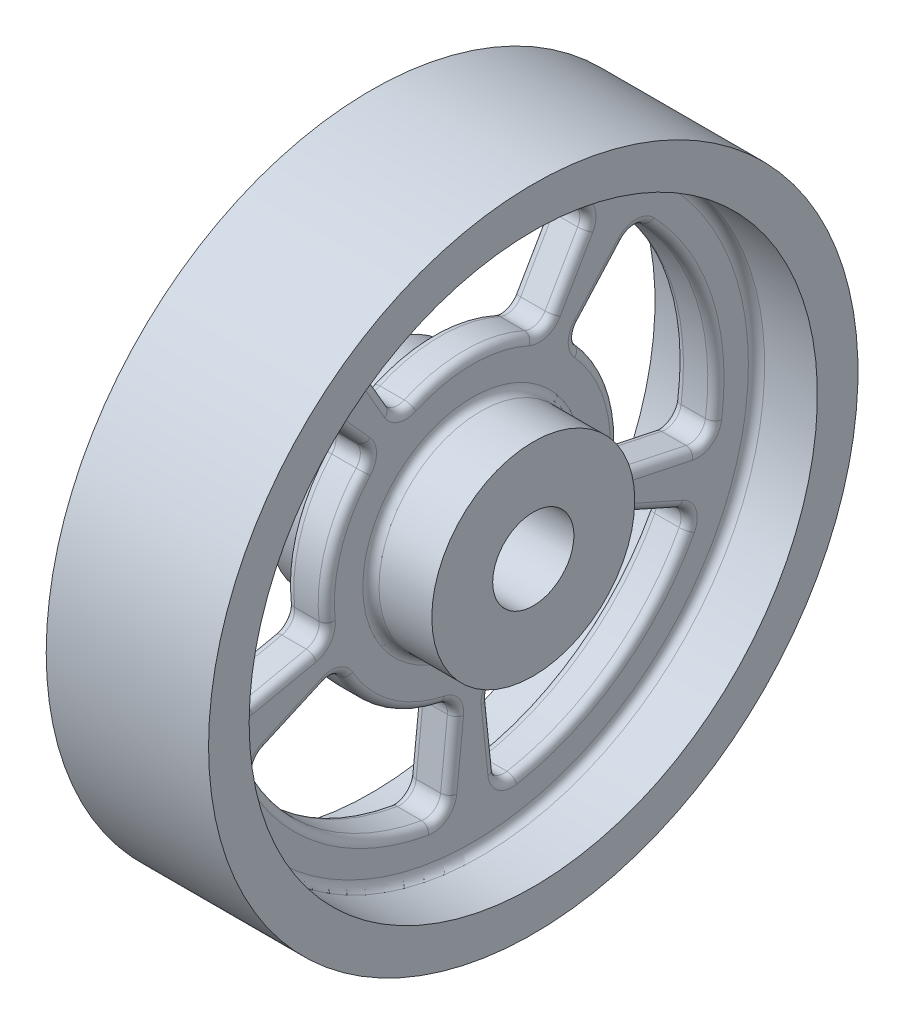
SolidWorks part; units mm, degrees
ref_plane "Front Plane" through (0, 0, 0) normal (0, 0, 1) x (1, 0, 0)
ref_plane "Top Plane" through (0, 0, 0) normal (0, 1, 0) x (1, 0, 0)
ref_plane "Right Plane" through (0, 0, 0) normal (1, 0, 0) x (0, 0, -1)
sketch "Sketch1" plane through (0, 0, 0) normal (0, 1, 0) x (1, 0, 0)
  line L0 (0, 0) -> (25.6742, 0) construction
  line L1 (0, 0) -> (0, 10.3933) construction
  line L2 (2.5, 35) -> (10, 35)
  line L3 (-10, 12.5) -> (-2.5, 12.5)
  line L4 (-10, 12.5) -> (-10, 5)
  line L5 (-10, 5) -> (10, 5)
  line L6 (10, 12.5) -> (10, 5)
  line L8 (-2.5, 12.5) -> (-2.5, 35)
  line L10 (2.5, 12.5) -> (2.5, 35)
  line L11 (-10, 40) -> (10, 40)
  line L12 (-10, 40) -> (-10, 35)
  line L13 (-10, 35) -> (-2.5, 35)
  line L14 (10, 40) -> (10, 35)
  line L15 (2.5, 12.5) -> (10, 12.5)
  dimension "D1" = 10
  dimension "D2" = 80
  dimension "D3" = 5
  dimension "D4" = 25
  dimension "D5" = 20
  dimension "D6" = 5
revolve "Revolve1" add sketch "Sketch1" angle 360 about L0
sketch "Sketch2" plane through (2.5, 0, 0) normal (1, 0, 0) x (0, 0, -1)
  line L0 (-9, 15.5885) -> (-15, 25.9808)
  line L2 (9, 15.5885) -> (15, 25.9808)
  line L3 (0, 18) -> (0, 34.3288) construction
  arc A0 (9, 15.5885) -> (-9, 15.5885) centre (0, 0) ccw
  arc A1 (15, 25.9808) -> (-15, 25.9808) centre (0, 0) ccw
  dimension "D1" = 60
  dimension "D2" = 30
  dimension "D3" = 18
extrude "Cut-Extrude1" cut sketch "Sketch2" against normal through all
fillet "Fillet1" radius 2 4 edges at (0, 25.9808, -15) (0, 15.5885, -9) (0, 25.9808, 15) (0, 15.5885, 9)
pattern_circular "CirPattern1" count 5 over 360 about axis through (0, 0, 0) along (1, 0, 0) of "Cut-Extrude1", "Fillet1"
fillet "Fillet2" radius 1 84 edges at (-2.5, 0, 35) (-2.5, 0, 12.5) (-2.5, 25.7731, -14.1443) (-2.5, 20.7102, -11.9571) (-2.5, 16.3302, -8.8315) (-2.5, 18, 0) (-2.5, 16.3302, 8.8315) (-2.5, 20.7102, 11.9571) (-2.5, 25.7731, 14.1443) (-2.5, 30, 0) (-2.5, -5.4877, -28.8825) (-2.5, -4.972, -23.3915) (-2.5, -3.353, -18.26) (-2.5, 5.5623, -17.119) (-2.5, 13.4456, -12.8018) (-2.5, 17.7717, -16.0017) (-2.5, 21.4164, -20.1409) (-2.5, 9.2705, -28.5317) (-2.5, -29.1647, -3.7061) (-2.5, -23.7831, -2.4997) (-2.5, -18.4024, -2.4538) (-2.5, -14.5623, -10.5801) (-2.5, -8.0203, -16.7435) (-2.5, -9.7267, -21.8466) (-2.5, -12.5371, -26.592) (-2.5, -24.2705, -17.6336) (-2.5, -12.5371, 26.592) (-2.5, -9.7267, 21.8466) (-2.5, -8.0203, 16.7435) (-2.5, -14.5623, 10.5801) (-2.5, -18.4024, 2.4538) (-2.5, -23.7831, 2.4997) (-2.5, -29.1647, 3.7061) (-2.5, -24.2705, 17.6336) (-2.5, 21.4164, 20.1409) (-2.5, 17.7717, 16.0017) (-2.5, 13.4456, 12.8018) (-2.5, 5.5623, 17.119) (-2.5, -3.353, 18.26) (-2.5, -4.972, 23.3915) (-2.5, -5.4877, 28.8825) (-2.5, 9.2705, 28.5317) (2.5, 0, 12.5) (2.5, 0, 35) (2.5, 25.7731, -14.1443) (2.5, 30, 0) (2.5, 25.7731, 14.1443) (2.5, 20.7102, 11.9571) (2.5, 16.3302, 8.8315) (2.5, 18, 0) (2.5, 16.3302, -8.8315) (2.5, 20.7102, -11.9571) (2.5, -5.4877, -28.8825) (2.5, 9.2705, -28.5317) (2.5, 21.4164, -20.1409) (2.5, 17.7717, -16.0017) (2.5, 13.4456, -12.8018) (2.5, 5.5623, -17.119) (2.5, -3.353, -18.26) (2.5, -4.972, -23.3915) (2.5, -29.1647, -3.7061) (2.5, -24.2705, -17.6336) (2.5, -12.5371, -26.592) (2.5, -9.7267, -21.8466) (2.5, -8.0203, -16.7435) (2.5, -14.5623, -10.5801) (2.5, -18.4024, -2.4538) (2.5, -23.7831, -2.4997) (2.5, -12.5371, 26.592) (2.5, -24.2705, 17.6336) (2.5, -29.1647, 3.7061) (2.5, -23.7831, 2.4997) (2.5, -18.4024, 2.4538) (2.5, -14.5623, 10.5801) (2.5, -8.0203, 16.7435) (2.5, -9.7267, 21.8466) (2.5, 21.4164, 20.1409) (2.5, 9.2705, 28.5317) (2.5, -5.4877, 28.8825) (2.5, -4.972, 23.3915) (2.5, -3.353, 18.26) (2.5, 5.5623, 17.119) (2.5, 13.4456, 12.8018) (2.5, 17.7717, 16.0017)
